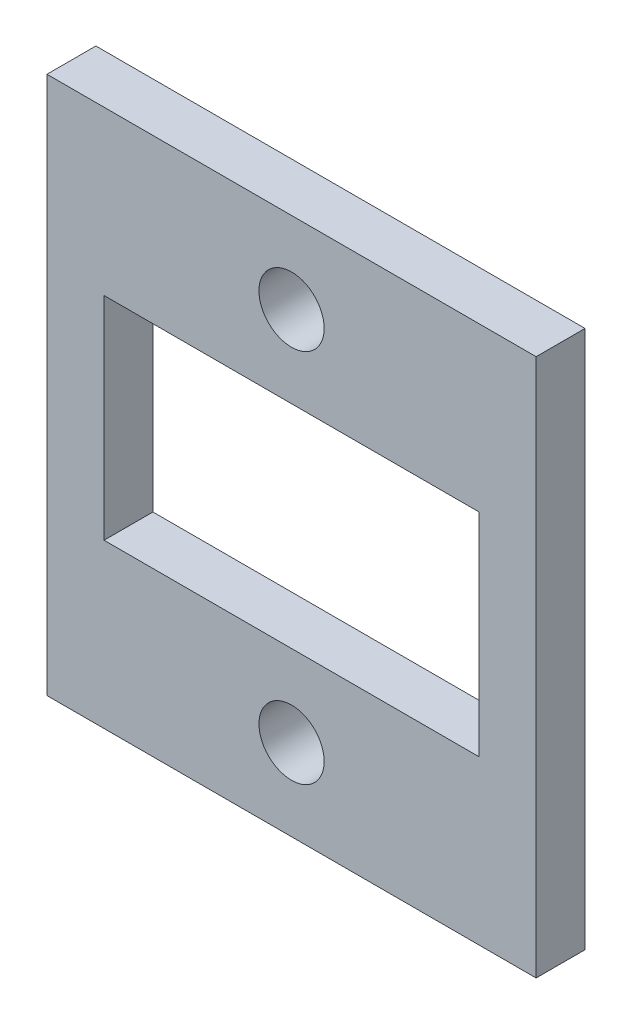
SolidWorks part; units mm, degrees
ref_plane "Front Plane" through (0, 0, 0) normal (0, 0, 1) x (1, 0, 0)
ref_plane "Top Plane" through (0, 0, 0) normal (0, 1, 0) x (1, 0, 0)
ref_plane "Right Plane" through (0, 0, 0) normal (1, 0, 0) x (0, 0, -1)
sketch "Sketch1" plane through (0, 0, 0) normal (0, 0, 1) x (1, 0, 0)
  line L1 (-15, 16.5) -> (15, 16.5)
  line L2 (-15, 16.5) -> (-15, -16.5)
  line L3 (-15, -16.5) -> (15, -16.5)
  line L4 (15, 16.5) -> (15, -16.5)
  line L5 (-15, 16.5) -> (15, -16.5) construction
  line L6 (-15, -16.5) -> (15, 16.5) construction
  point P0 (0, 0)
  dimension "D1" = 30
  dimension "D2" = 33
extrude "Boss-Extrude1" add sketch "Sketch1" along normal blind 3
sketch "Sketch2" plane through (0, 0, 3) normal (0, 0, 1) x (1, 0, 0)
  line L1 (-11.5, 6.5) -> (11.5, 6.5)
  line L2 (-11.5, 6.5) -> (-11.5, -6.5)
  line L3 (-11.5, -6.5) -> (11.5, -6.5)
  line L4 (11.5, 6.5) -> (11.5, -6.5)
  line L5 (-11.5, 6.5) -> (11.5, -6.5) construction
  line L6 (-11.5, -6.5) -> (11.5, 6.5) construction
  point P0 (0, 0)
  dimension "D1" = 23
  dimension "D2" = 13
extrude "Cut-Extrude1" cut sketch "Sketch2" against normal through all
sketch "Sketch3" plane through (0, 0, 3) normal (0, 0, 1) x (1, 0, 0)
  line L0 (15, 16.5) -> (-15, 16.5) construction
  line L1 (15, -16.5) -> (15, 16.5) construction
  circle A0 centre (0, 11.5) radius 2
  circle A1 centre (0, -11.5) radius 2
  dimension "D1" = 4
  dimension "D2" = 4
  dimension "D3" = 5
  dimension "D4" = 15
  dimension "D6" = 15
extrude "Cut-Extrude2" cut sketch "Sketch3" against normal blind 3
sketch "Sketch4" plane through (0, 0, 3) normal (0, 0, 1) x (1, 0, 0)
